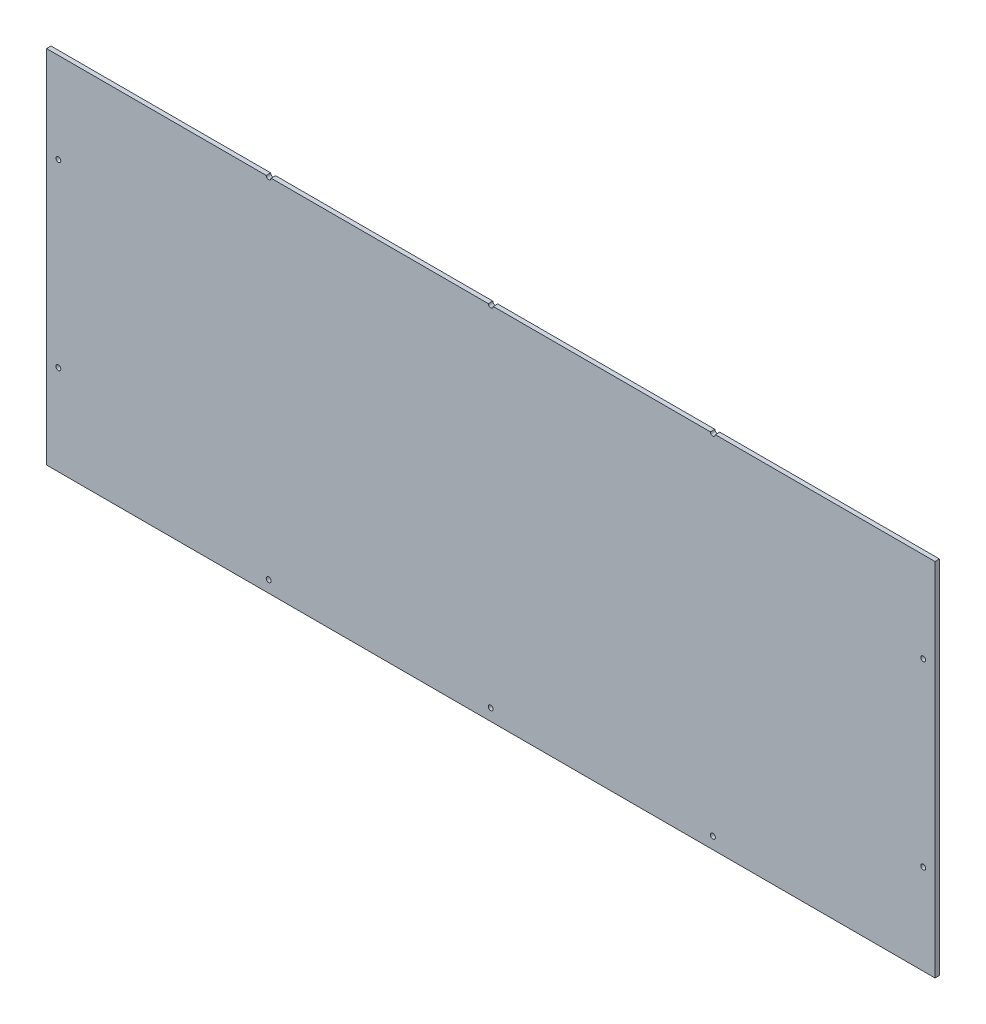
SolidWorks part; units mm, degrees
ref_plane "Front Plane" through (0, 0, 0) normal (0, 0, 1) x (1, 0, 0)
ref_plane "Top Plane" through (0, 0, 0) normal (0, 1, 0) x (1, 0, 0)
ref_plane "Right Plane" through (0, 0, 0) normal (1, 0, 0) x (0, 0, -1)
sketch "Sketch2" plane through (0, 0, 0) normal (0, 0, 1) x (1, 0, 0)
  line L0 (2.5, 183.5) -> (223.5, 183.5)
  line L1 (-452, 183.5) -> (-228.5, 183.5)
  line L2 (-452, 183.5) -> (-452, -183.5)
  line L3 (-452, -183.5) -> (452, -183.5)
  line L4 (452, 183.5) -> (452, -183.5)
  line L5 (-223.5, 183.5) -> (-2.5, 183.5)
  line L6 (228.5, 183.5) -> (452, 183.5)
  line L7 (-452, 0) -> (452, 0) construction
  line L8 (0, 181) -> (0, -183.5) construction
  arc A0 (-2.5, 183.5) -> (2.5, 183.5) centre (0, 183.5) ccw
  arc A1 (223.5, 183.5) -> (228.5, 183.5) centre (226, 183.5) ccw
  arc A2 (-228.5, 183.5) -> (-223.5, 183.5) centre (-226, 183.5) ccw
  circle A5 centre (0, -171.5) radius 2.5
  circle A6 centre (226, -171.5) radius 2.5
  circle A7 centre (-226, -171.5) radius 2.5
  circle A8 centre (-440, 91.75) radius 2.5
  circle A9 centre (-440, -91.75) radius 2.5
  circle A10 centre (440, -91.75) radius 2.5
  circle A12 centre (440, 91.75) radius 2.5
  dimension "D5" = 2
  dimension "D6" = 12
  dimension "D7" = 12
  dimension "D8" = 2
  dimension "D1" = 904
  dimension "D2" = 367
  dimension "D3" = 452
  dimension "D4" = 183.5
  dimension "D9" = 12
extrude "Boss-Extrude1" add sketch "Sketch2" along normal blind 4.5
